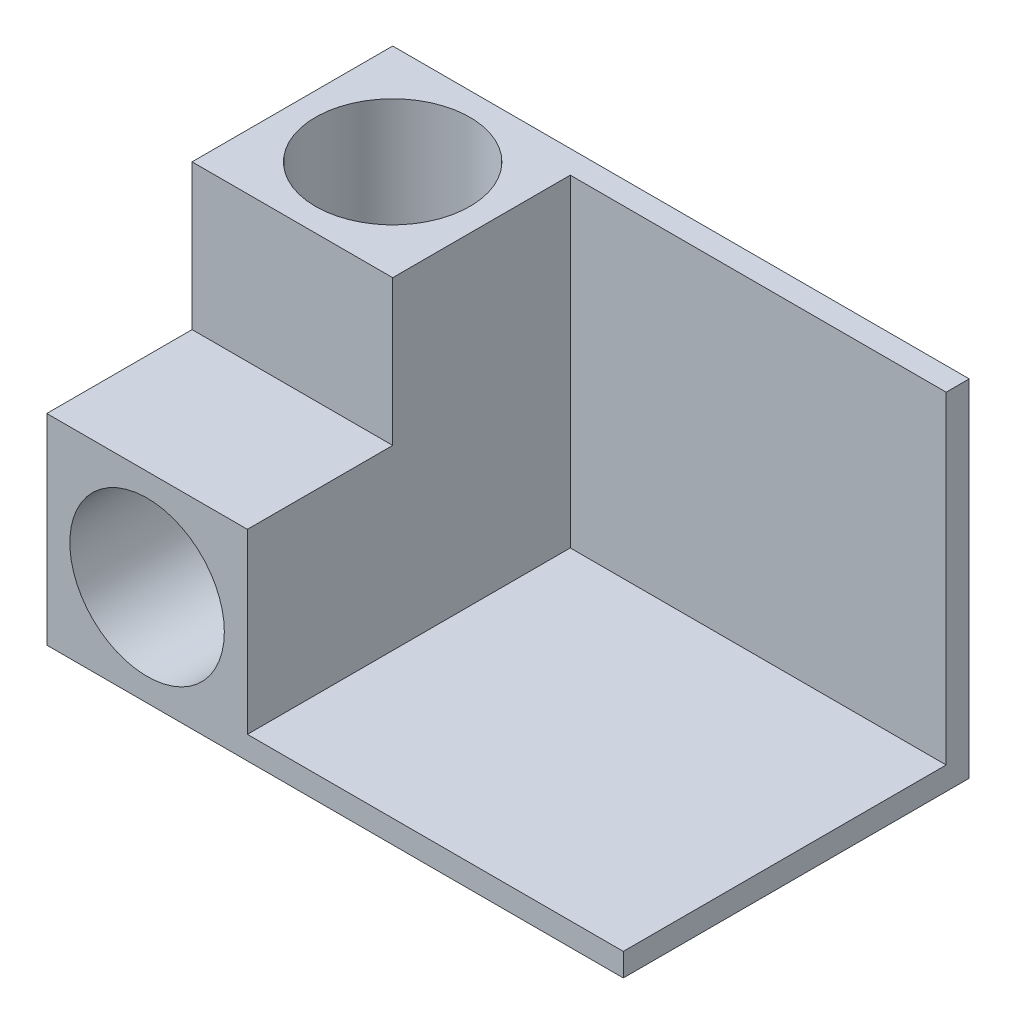
SolidWorks part; units mm, degrees
ref_plane "Front Plane" through (0, 0, 0) normal (0, 0, 1) x (1, 0, 0)
ref_plane "Top Plane" through (0, 0, 0) normal (0, 1, 0) x (1, 0, 0)
ref_plane "Right Plane" through (0, 0, 0) normal (1, 0, 0) x (0, 0, -1)
sketch "Sketch1" plane through (0, 0, 0) normal (0, 1, 0) x (1, 0, 0)
  line L0 (-65.2, 44.6799) -> (-65.2, -11.3201)
  line L1 (0, -11.3201) -> (-100, -11.3201)
  line L2 (0, -11.3201) -> (0, 48.6799)
  line L3 (0, 48.6799) -> (-100, 48.6799)
  line L4 (-100, -11.3201) -> (-100, 48.6799)
  line L5 (-65.2, 44.6799) -> (0, 44.6799)
  circle A0 centre (-82.6, 31.2799) radius 13.4
  dimension "D3" = 17.4
  dimension "D4" = 17.4
  dimension "D5" = 26.8
  dimension "D1" = 100
  dimension "D2" = 60
  dimension "D6" = 34.8
  dimension "D7" = 4
extrude "Boss-Extrude1" add sketch "Sketch1" along normal blind 56 contours L0 L5 L2 L3 L4 L1 A0
sketch "Sketch2" plane through (0, 0, 0) normal (0, 1, 0) x (1, 0, 0)
  line L1 (0, 48.6799) -> (-100, 48.6799)
  line L2 (0, 48.6799) -> (0, -11.3201)
  line L3 (0, -11.3201) -> (-100, -11.3201)
  line L4 (-100, 48.6799) -> (-100, -11.3201)
extrude "Boss-Extrude2" add sketch "Sketch2" against normal blind 4
sketch "Sketch3" plane through (0, 0, 11.3201) normal (0, 0, 1) x (1, 0, 0)
  line L0 (-100, 56) -> (-100, -4) construction
  line L2 (-100, -4) -> (0, -4) construction
  circle A0 centre (-82.6, 13.4) radius 13.4
  dimension "D2" = 17.4
  dimension "D3" = 26.8
  dimension "D1" = 17.4
extrude "Cut-Extrude1" cut sketch "Sketch3" against normal blind 25.2 contours A0
sketch "Sketch4" plane through (-100, 0, 0) normal (-1, 0, 0) x (0, 0, 1)
  line L0 (-48.6799, -4) -> (11.3201, -4) construction
  line L9 (11.3201, 56) -> (-13.8799, 56)
  line L10 (11.3201, 56) -> (11.3201, 30.8)
  line L11 (11.3201, 30.8) -> (-13.8799, 30.8)
  line L12 (-13.8799, 56) -> (-13.8799, 30.8)
  line L13 (-48.6799, 56) -> (-48.6799, -4) construction
  dimension "D1" = 34.8
  dimension "D3" = 34.8
extrude "Cut-Extrude2" cut sketch "Sketch4" against normal blind 51.2
